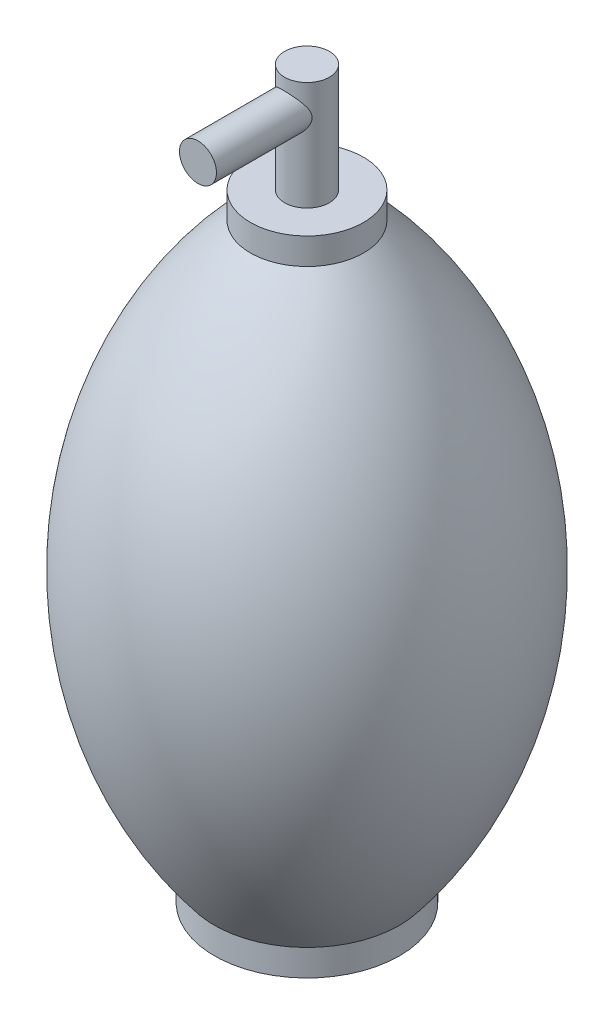
SolidWorks part; units mm, degrees
ref_plane "Front Plane" through (0, 0, 0) normal (0, 0, 1) x (1, 0, 0)
ref_plane "Top Plane" through (0, 0, 0) normal (0, 1, 0) x (1, 0, 0)
ref_plane "Right Plane" through (0, 0, 0) normal (1, 0, 0) x (0, 0, -1)
sketch "Sketch1" plane through (0, 0, 0) normal (0, 0, 1) x (1, 0, 0)
  line L0 (-13.9421, 14.1189) -> (-33.1921, 14.1189)
  line L1 (-33.1921, 14.1189) -> (-33.1921, 5.1189)
  line L2 (-33.1921, 5.1189) -> (-33.1921, -186.8811)
  line L3 (-33.1921, -186.8811) -> (-33.1921, -195.8811)
  line L4 (-33.1921, -195.8811) -> (-1.6921, -195.8811)
  line L5 (-13.9421, 14.1189) -> (-13.9421, 5.1189)
  line L7 (-1.6921, -195.8811) -> (-1.6921, -186.8811)
  arc A0 (-13.9421, 5.1189) -> (-1.6921, -186.8811) centre (-113.8811, -97.6482) cw
  dimension "D1" = 9
  dimension "D2" = 210
  dimension "D3" = 9
  dimension "D4" = 19.25
  dimension "D5" = 31.5
  dimension "D7" = 0
  dimension "D8" = 0
revolve "Revolve1" add sketch "Sketch1" angle 360 about L2
sketch "Sketch2" plane through (0, 14.1189, 0) normal (0, 1, 0) x (1, 0, 0)
  circle A0 centre (-33.1921, 0) radius 7.6214
extrude "Boss-Extrude1" add sketch "Sketch2" along normal blind 37
sketch "Sketch3" plane through (0, 0, 0) normal (0, 0, 1) x (1, 0, 0)
  circle A0 centre (-33.3054, 40.7179) radius 6.3013
extrude "Boss-Extrude2" add sketch "Sketch3" along normal blind 37
